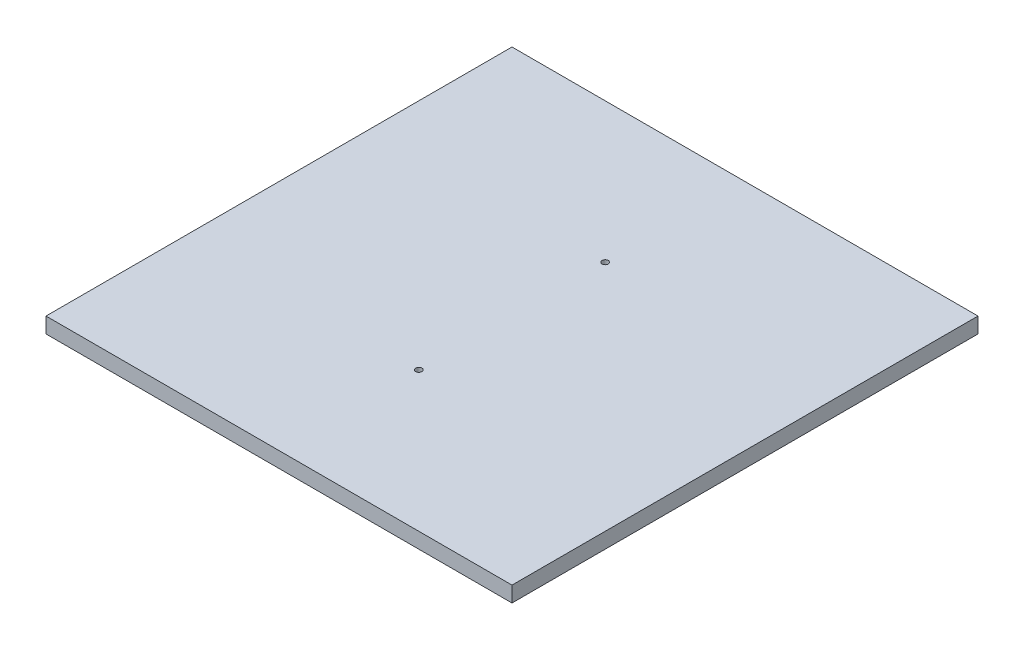
SolidWorks part; units mm, degrees
ref_plane "Front Plane" through (0, 0, 0) normal (0, 0, 1) x (1, 0, 0)
ref_plane "Top Plane" through (0, 0, 0) normal (0, 1, 0) x (1, 0, 0)
ref_plane "Right Plane" through (0, 0, 0) normal (1, 0, 0) x (0, 0, -1)
sketch "Sketch1" plane through (0, 0, 0) normal (0, 1, 0) x (1, 0, 0)
  line L1 (-75, -75) -> (75, -75)
  line L2 (-75, -75) -> (-75, 75)
  line L3 (-75, 75) -> (75, 75)
  line L4 (75, -75) -> (75, 75)
  line L5 (-75, -75) -> (75, 75) construction
  line L6 (-75, 75) -> (75, -75) construction
  circle A0 centre (0, 30) radius 1
  circle A1 centre (0, -30) radius 1
  point P0 (0, 0)
  dimension "D3" = 2
  dimension "D4" = 30
  dimension "D5" = 30
  dimension "D1" = 150
  dimension "D2" = 150
extrude "Boss-Extrude1" add sketch "Sketch1" along normal blind 5
